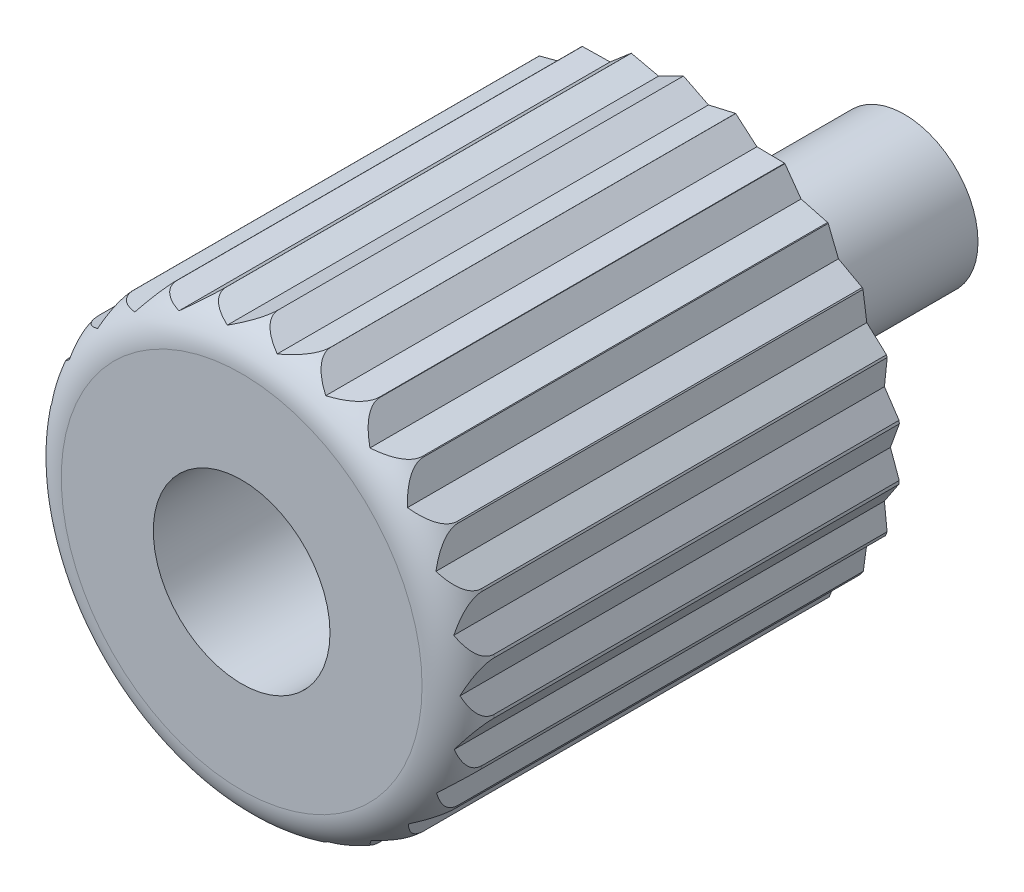
SolidWorks part; units mm, degrees
ref_plane "Alzado" through (0, 0, 0) normal (0, 0, 1) x (1, 0, 0)
ref_plane "Planta" through (0, 0, 0) normal (0, 1, 0) x (1, 0, 0)
ref_plane "Vista lateral" through (0, 0, 0) normal (1, 0, 0) x (0, 0, -1)
sketch "Croquis1" plane through (0, 0, 0) normal (0, 0, 1) x (1, 0, 0)
  circle A0 centre (0, 0) radius 1
  dimension "D1" = 2
extrude "Saliente-Extruir1" add sketch "Croquis1" along normal blind 3
sketch "Croquis2" plane through (0, 0, 3) normal (0, 0, 1) x (1, 0, 0)
  circle A0 centre (0, 0) radius 2.95
  dimension "D1" = 5.9
extrude "Saliente-Extruir2" add sketch "Croquis2" along normal blind 6
fillet "Redondeo2" radius 0.5 1 edges at (2.95, 0, 9)
sketch "Croquis3" plane through (0, 0, 9) normal (0, 0, 1) x (1, 0, 0)
  circle A0 centre (0, 0) radius 1.2
  dimension "D1" = 2.4
extrude "Cortar-Extruir2" cut sketch "Croquis3" against normal blind 5
sketch "Croquis4" plane through (0, 0, 9) normal (0, 0, 1) x (1, 0, 0)
  line L0 (0, -2.95) -> (0, 2.95) construction
  line L1 (-0.3379, 2.7795) -> (0, 2.95)
  line L2 (0, 2.95) -> (0.3398, 2.7793)
  line L3 (0.3398, 2.7793) -> (0.7086, 2.864)
  line L4 (0.7086, 2.864) -> (0.9977, 2.6169)
  line L5 (0.9977, 2.6169) -> (1.3761, 2.6108)
  line L6 (1.3761, 2.6108) -> (1.5976, 2.3018)
  line L7 (1.5976, 2.3018) -> (1.9636, 2.2053)
  line L8 (1.9636, 2.2053) -> (2.1047, 1.8522)
  line L9 (2.1047, 1.8522) -> (2.437, 1.671)
  line L10 (2.437, 1.671) -> (2.4895, 1.2944)
  line L11 (2.4895, 1.2944) -> (2.7687, 1.0389)
  line L12 (2.7687, 1.0389) -> (2.7296, 0.6607)
  line L13 (2.7296, 0.6607) -> (2.9395, 0.3458)
  line L14 (2.9395, 0.3458) -> (2.811, -0.0121)
  line L15 (2.811, -0.0121) -> (2.9395, -0.3681)
  line L16 (2.9395, -0.3681) -> (2.7291, -0.6848)
  line L17 (2.7291, -0.6848) -> (2.7687, -1.0612)
  line L18 (2.7687, -1.0612) -> (2.4886, -1.3183)
  line L19 (2.4886, -1.3183) -> (2.437, -1.6932)
  line L20 (2.437, -1.6932) -> (2.1035, -1.8759)
  line L21 (2.1035, -1.8759) -> (1.9636, -2.2276)
  line L22 (1.9636, -2.2276) -> (1.5961, -2.3251)
  line L23 (1.5961, -2.3251) -> (1.3761, -2.6331)
  line L24 (1.3761, -2.6331) -> (0.9959, -2.6398)
  line L25 (0.9959, -2.6398) -> (0.7086, -2.8862)
  line L26 (0.7086, -2.8862) -> (0.3379, -2.8018)
  line L27 (0.3379, -2.8018) -> (0, -2.9723)
  line L28 (0, -2.9723) -> (-0.3398, -2.8016)
  line L29 (-0.3398, -2.8016) -> (-0.7087, -2.8862)
  line L30 (-0.7087, -2.8862) -> (-0.9977, -2.6392)
  line L31 (-0.9977, -2.6392) -> (-1.3761, -2.6331)
  line L32 (-1.3761, -2.6331) -> (-1.5977, -2.324)
  line L33 (-1.5977, -2.324) -> (-1.9636, -2.2276)
  line L34 (-1.9636, -2.2276) -> (-2.1047, -1.8745)
  line L35 (-2.1047, -1.8745) -> (-2.437, -1.6932)
  line L36 (-2.437, -1.6932) -> (-2.4895, -1.3166)
  line L37 (-2.4895, -1.3166) -> (-2.7687, -1.0612)
  line L38 (-2.7687, -1.0612) -> (-2.7296, -0.6829)
  line L39 (-2.7296, -0.6829) -> (-2.9395, -0.368)
  line L40 (-2.9395, -0.368) -> (-2.8111, -0.0102)
  line L41 (-2.8111, -0.0102) -> (-2.9395, 0.3458)
  line L42 (-2.9395, 0.3458) -> (-2.7291, 0.6625)
  line L43 (-2.7291, 0.6625) -> (-2.7687, 1.0389)
  line L44 (-2.7687, 1.0389) -> (-2.4886, 1.2961)
  line L45 (-2.4886, 1.2961) -> (-2.437, 1.671)
  line L46 (-2.437, 1.671) -> (-2.1035, 1.8537)
  line L47 (-2.1035, 1.8537) -> (-1.9636, 2.2053)
  line L48 (-1.9636, 2.2053) -> (-1.5961, 2.3029)
  line L49 (-1.5961, 2.3029) -> (-1.3761, 2.6108)
  line L50 (-1.3761, 2.6108) -> (-0.9959, 2.6176)
  line L51 (-0.9959, 2.6176) -> (-0.7086, 2.864)
  line L52 (-0.7086, 2.864) -> (-0.3379, 2.7795)
  circle A0 centre (0, 0) radius 2.8 construction
  circle A1 centre (0, 0) radius 2.95 construction
  circle A2 centre (0, 0) radius 3.595
  point P88 (0, -0.0111)
  dimension "D1" = 5.6
  dimension "D2" = 26
extrude "Cortar-Extruir3" cut sketch "Croquis4" against normal through all
